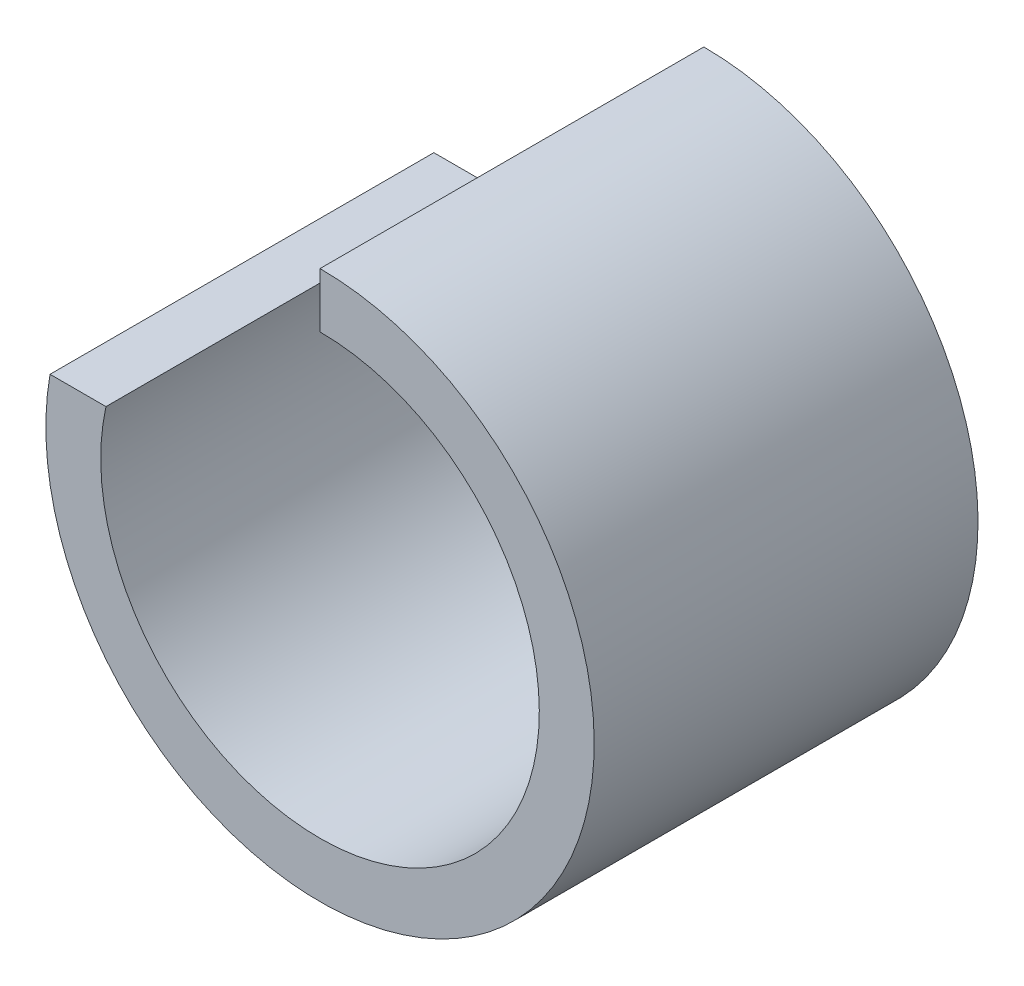
SolidWorks part; units mm, degrees
ref_plane "Front Plane" through (0, 0, 0) normal (0, 0, 1) x (1, 0, 0)
ref_plane "Top Plane" through (0, 0, 0) normal (0, 1, 0) x (1, 0, 0)
ref_plane "Right Plane" through (0, 0, 0) normal (1, 0, 0) x (0, 0, -1)
sketch "Sketch1" plane through (0, 0, 0) normal (0, 0, 1) x (1, 0, 0)
  line L2 (0, 10) -> (0, 7.9981)
  line L3 (-9.8481, 1.7365) -> (-7.8073, 1.7365)
  arc A0 (-7.8073, 1.7365) -> (0, 7.9981) centre (0, 0) ccw
  arc A1 (-9.8481, 1.7365) -> (0, 10) centre (0, 0) ccw
  point P3 (0, 0)
  point P8 (-7.8073, 1.7365)
  point P9 (-7.8203, 1.7365)
extrude "Boss-Extrude1" add sketch "Sketch1" along normal blind 14
